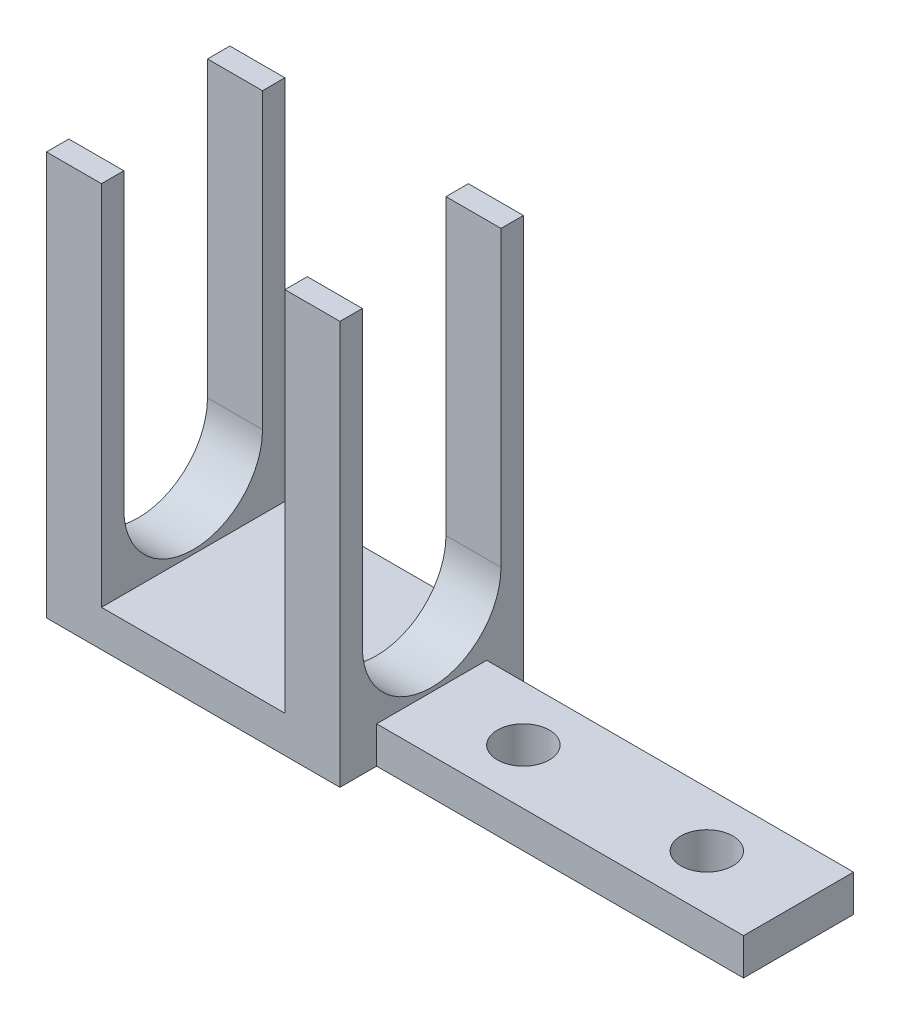
SolidWorks part; units mm, degrees
ref_plane "Front Plane" through (0, 0, 0) normal (0, 0, 1) x (1, 0, 0)
ref_plane "Top Plane" through (0, 0, 0) normal (0, 1, 0) x (1, 0, 0)
ref_plane "Right Plane" through (0, 0, 0) normal (1, 0, 0) x (0, 0, -1)
sketch "Sketch1" plane through (0, 0, 0) normal (0, 1, 0) x (1, 0, 0)
  line L1 (-15.875, -4.7625) -> (15.875, -4.7625)
  line L2 (-15.875, -4.7625) -> (-15.875, 4.7625)
  line L3 (-15.875, 4.7625) -> (15.875, 4.7625)
  line L4 (15.875, -4.7625) -> (15.875, 4.7625)
  line L5 (-15.875, -4.7625) -> (15.875, 4.7625) construction
  line L6 (-15.875, 4.7625) -> (15.875, -4.7625) construction
  point P0 (0, 0)
  dimension "D1" = 9.525
  dimension "D2" = 31.75
extrude "Boss-Extrude1" add sketch "Sketch1" along normal blind 3.175
hole_wizard "#8 Clearance Hole1" positions "Sketch2" profile "Sketch3" hole size "#8" standard "ANSI Inch" end condition through all
sketch "Sketch2" plane through (0, 3.175, 0) normal (0, 1, 0) x (1, 0, 0)
  point P0 (-7.9375, 0)
  point P2 (7.9375, 0)
  dimension "D1" = 15.875
  dimension "D2" = 7.9375
sketch "Sketch3" plane through (-7.9375, 3.175, 0) normal (1, 0, 0) x (0, 0, 1)
  line L0 (0, 0) -> (0, 3.175)
  line L1 (0, 3.175) -> (2.2479, 3.175)
  line L2 (2.2479, 3.175) -> (2.2479, 0)
  line L5 (2.2479, 0) -> (0, 0)
  line L11 (0, -6.35) -> (0, 107.95) construction
  dimension "Thru Hole Dia." = 4.4958
  dimension "Thru Hole Depth" = 3.175
sketch "Sketch4" plane through (0, 0, 0) normal (0, 1, 0) x (1, 0, 0)
  line L5 (-15.875, 4.7625) -> (-15.875, -4.7625) construction
  line L6 (-41.275, -7.9375) -> (-15.875, -7.9375)
  line L7 (-41.275, -7.9375) -> (-41.275, 7.9375)
  line L8 (-41.275, 7.9375) -> (-15.875, 7.9375)
  line L9 (-15.875, -7.9375) -> (-15.875, 7.9375)
  line L10 (-41.275, -7.9375) -> (-15.875, 7.9375) construction
  line L11 (-41.275, 7.9375) -> (-15.875, -7.9375) construction
  point P0 (-28.575, 0)
  dimension "D1" = 15.875
  dimension "D2" = 25.4
  dimension "D3" = 0
  dimension "D4" = 7.9375
extrude "Boss-Extrude2" add sketch "Sketch4" along normal blind 3.175
sketch "Sketch5" plane through (0, 3.175, 0) normal (0, 1, 0) x (1, 0, 0)
  line L6 (-41.275, -7.9375) -> (-15.875, -7.9375) construction
  line L7 (-41.275, 7.9375) -> (-36.5125, 7.9375)
  line L8 (-41.275, 7.9375) -> (-41.275, -7.9375)
  line L9 (-41.275, -7.9375) -> (-36.5125, -7.9375)
  line L10 (-36.5125, 7.9375) -> (-36.5125, -7.9375)
  dimension "D1" = 4.7625
extrude "Boss-Extrude3" add sketch "Sketch5" along normal blind 31.75
sketch "Sketch7" plane through (-41.275, 0, 0) normal (-1, 0, 0) x (0, 0, 1)
  line L0 (0, 34.925) -> (0, 9.525) construction
  line L1 (-7.9375, 34.925) -> (7.9375, 34.925) construction
  line L2 (6, 34.925) -> (6, 9.525)
  line L3 (-6, 34.925) -> (-6, 9.525)
  arc A0 (6, 34.925) -> (-6, 34.925) centre (0, 34.925) ccw
  arc A1 (-6, 9.525) -> (6, 9.525) centre (0, 9.525) ccw
  point P5 (0, 22.225)
  dimension "D1" = 6
  dimension "D2" = 25.4
extrude "Cut-Extrude1" cut sketch "Sketch7" against normal through all contours A1 L2 A0 L3
pattern_linear "LPattern1" count 2 spacing 20.6375 along (1, 0, 0) of "Cut-Extrude1", "Boss-Extrude3"
